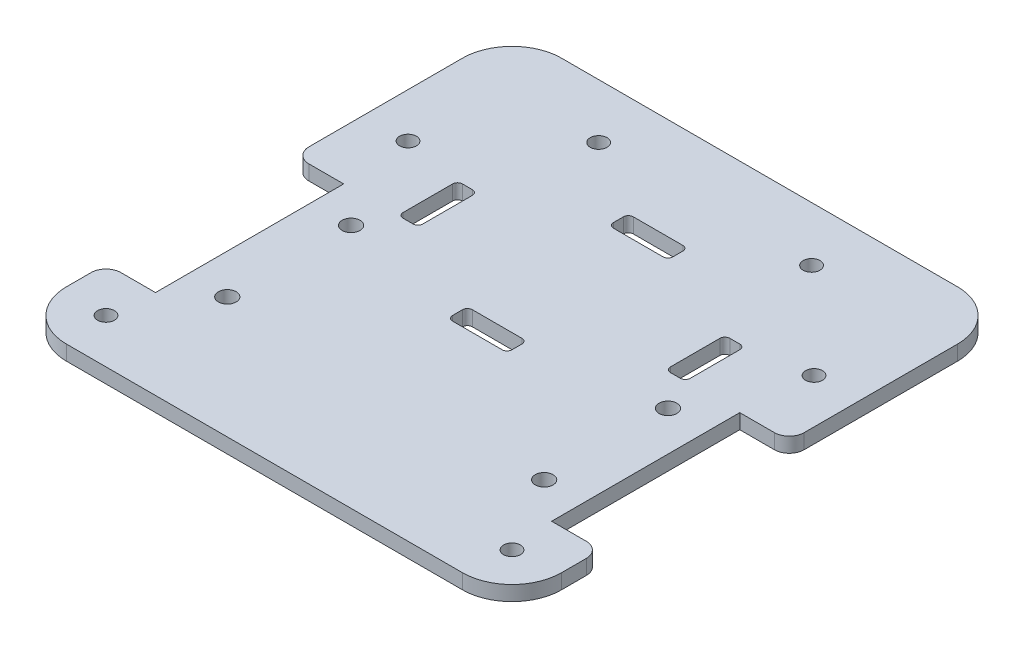
SolidWorks part; units mm, degrees
ref_plane "Front Plane" through (0, 0, 0) normal (0, 0, 1) x (1, 0, 0)
ref_plane "Top Plane" through (0, 0, 0) normal (0, 1, 0) x (1, 0, 0)
ref_plane "Right Plane" through (0, 0, 0) normal (1, 0, 0) x (0, 0, -1)
sketch "Sketch1" plane through (0, 0, 0) normal (0, 1, 0) x (1, 0, 0)
  line L1 (-50, 50) -> (50, 50)
  line L2 (-50, 50) -> (-50, -50)
  line L3 (-50, -50) -> (50, -50)
  line L4 (50, 50) -> (50, -50)
  line L5 (-50, 50) -> (50, -50) construction
  line L6 (-50, -50) -> (50, 50) construction
  point P0 (0, 0)
  dimension "D1" = 100
  dimension "D2" = 100
extrude "Boss-Extrude1" add sketch "Sketch1" along normal blind 3 contours L2 L3 L4 L1
sketch "Sketch2" plane through (0, 3, 0) normal (0, 1, 0) x (1, 0, 0)
  line L0 (-50, 50) -> (-50, -50) construction
  line L1 (-50, -32) -> (-40, -32)
  line L2 (-50, -32) -> (-50, 6)
  line L3 (-50, 6) -> (-40, 6)
  line L4 (-40, -32) -> (-40, 6)
  line L5 (-50, -50) -> (50, -50) construction
  dimension "D1" = 18
  dimension "D2" = 38
  dimension "D3" = 10
sketch "Sketch4" plane through (0, 3, 0) normal (0, 1, 0) x (1, 0, 0)
  circle A0 centre (-41, 20) radius 1.7
  circle A1 centre (-41, -41) radius 1.7
  circle A2 centre (41, -41) radius 1.7
  circle A3 centre (41, 20) radius 1.7
extrude "Cut-Extrude3" cut sketch "Sketch4" against normal up to surface (3 mm away) up to face at (0, 0, 0)
extrude "Cut-Extrude4" cut sketch "Sketch2" against normal up to surface (3 mm away) up to face at (41, 0, -21.7)
mirror "Mirror2" about plane through (0, 0, 0) normal (1, 0, 0) of "Cut-Extrude4"
sketch "Sketch5" plane through (0, 3, 0) normal (0, 1, 0) x (1, 0, 0)
  line L0 (-50, -50) -> (50, -50) construction
  line L1 (-6, -3) -> (6, -3)
  line L2 (-6, -3) -> (-6, -7)
  line L3 (-6, -7) -> (6, -7)
  line L4 (6, -3) -> (6, -7)
  line L5 (-6, -3) -> (6, -7) construction
  line L6 (-6, -7) -> (6, -3) construction
  line L7 (50, 50) -> (50, 6) construction
  line L8 (-50, 50) -> (-50, 6) construction
  line L9 (-50, 50) -> (50, 50) construction
  line L10 (-6, 29.5) -> (6, 29.5)
  line L11 (-6, 29.5) -> (-6, 25.5)
  line L12 (-6, 25.5) -> (6, 25.5)
  line L13 (6, 29.5) -> (6, 25.5)
  line L14 (-6, 29.5) -> (6, 25.5) construction
  line L15 (-6, 25.5) -> (6, 29.5) construction
  line L16 (-29, 18) -> (-25, 18)
  line L17 (-29, 18) -> (-29, 6)
  line L18 (-29, 6) -> (-25, 6)
  line L19 (-25, 18) -> (-25, 6)
  line L20 (-29, 18) -> (-25, 6) construction
  line L21 (-29, 6) -> (-25, 18) construction
  line L22 (25, 18) -> (29, 18)
  line L23 (25, 18) -> (25, 6)
  line L24 (25, 6) -> (29, 6)
  line L25 (29, 18) -> (29, 6)
  line L26 (25, 18) -> (29, 6) construction
  line L27 (25, 6) -> (29, 18) construction
  circle A0 centre (-32, -0.5) radius 1.8
  circle A1 centre (-32, -25.5) radius 1.8
  circle A3 centre (32, -25.5) radius 1.8
  circle A5 centre (32, -0.5) radius 1.8
  circle A6 centre (-21.5, 39) radius 1.7
  circle A7 centre (21.5, 39) radius 1.7
  point P0 (0, -5)
  point P11 (0, 27.5)
  point P16 (-6, 27.5)
  point P17 (-27, 12)
  point P22 (27, 12)
  dimension "D1" = 43
  dimension "D2" = 44
  dimension "D3" = 44
  dimension "D4" = 4
  dimension "D5" = 4
  dimension "D6" = 12
  dimension "D7" = 44
  dimension "D8" = 28.5
  dimension "D9" = 4
  dimension "D10" = 12
  dimension "D11" = 21
  dimension "D12" = 21
  dimension "D13" = 4
  dimension "D14" = 32
  dimension "D15" = 32
  dimension "D16" = 12
extrude "Cut-Extrude5" cut sketch "Sketch5" against normal up to surface (3 mm away) up to face at (0, 0, 8.6667)
fillet "Fillet1" radius 10 2 edges at (-50, 1.5, 50) (50, 1.5, 50)
fillet "Fillet2" radius 3 2 edges at (50, 1.5, 32) (50, 1.5, -6)
fillet "Fillet3" radius 10 2 edges at (-50, 1.5, -50) (50, 1.5, -50)
fillet "Fillet4" radius 3 1 edges at (-50, 1.5, 32)
fillet "Fillet5" radius 3 1 edges at (-50, 1.5, -6)
fillet "Fillet6" radius 1 16 edges at (-29, 1.5, -6) (-29, 1.5, -18) (-25, 1.5, -18) (-25, 1.5, -6) (-6, 1.5, 7) (-6, 1.5, 3) (6, 1.5, 7) (6, 1.5, 3) (25, 1.5, -6) (29, 1.5, -6) (25, 1.5, -18) (29, 1.5, -18) (-6, 1.5, -25.5) (6, 1.5, -25.5) (6, 1.5, -29.5) (-6, 1.5, -29.5)
